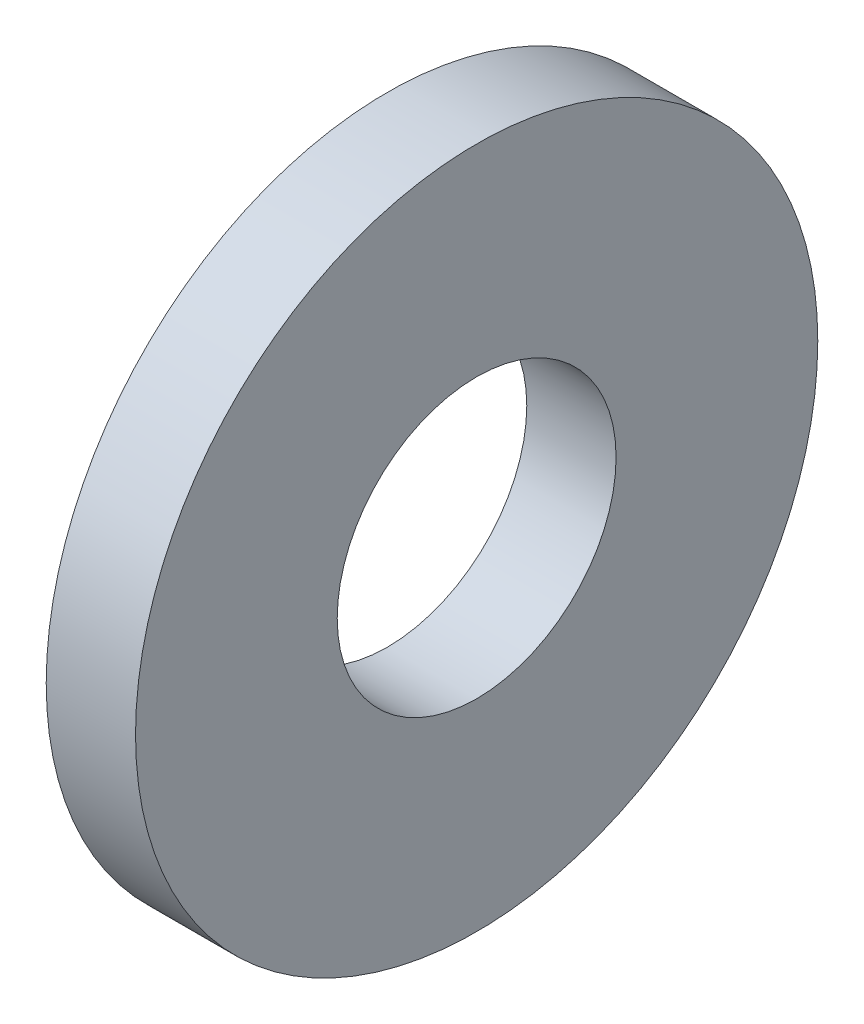
SolidWorks part; units mm, degrees
ref_plane "Front Plane" through (0, 0, 0) normal (0, 0, 1) x (1, 0, 0)
ref_plane "Top Plane" through (0, 0, 0) normal (0, 1, 0) x (1, 0, 0)
ref_plane "Right Plane" through (0, 0, 0) normal (1, 0, 0) x (0, 0, -1)
sketch "Sketch1" plane through (0, 0, 0) normal (1, 0, 0) x (0, 0, -1)
  circle A0 centre (0, 0) radius 8.7312
  circle A1 centre (0, 0) radius 3.5687
  dimension "OD" = 17.4625
  dimension "ID" = 7.1374
extrude "Boss-Extrude1" add sketch "Sketch1" along normal blind 2.286
